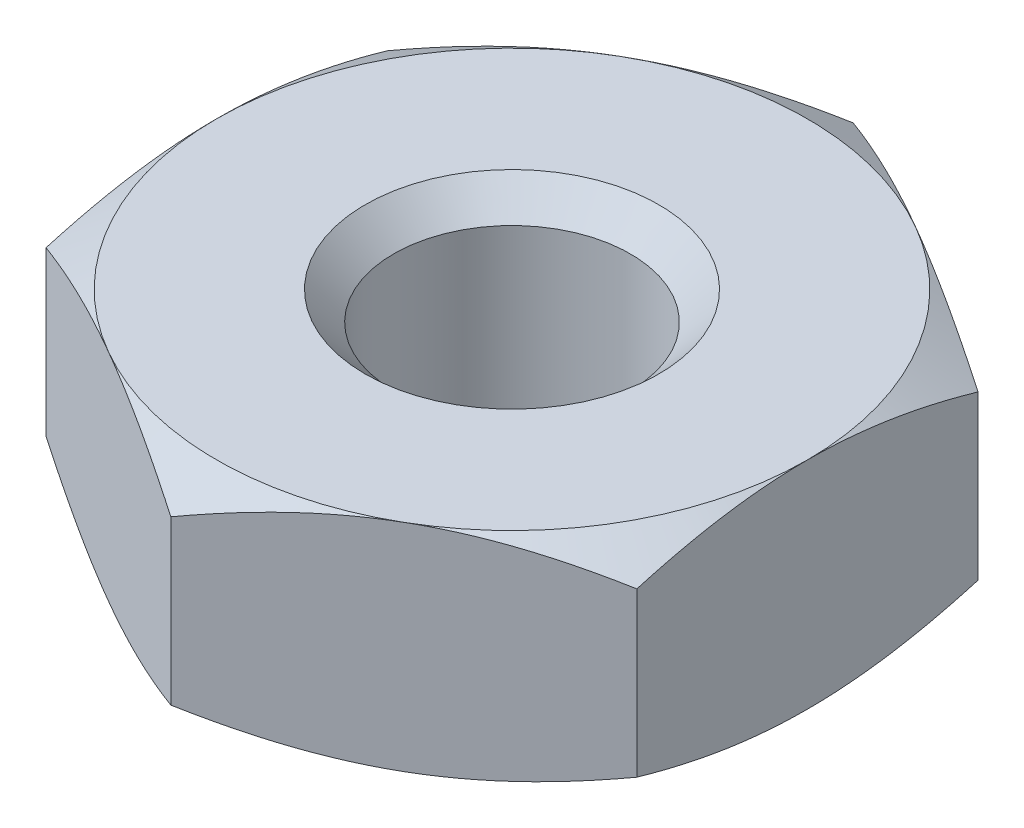
SolidWorks part; units mm, degrees
material "AISI 1020"
ref_plane "Front Plane" through (0, 0, 0) normal (0, 0, 1) x (1, 0, 0)
ref_plane "Top Plane" through (0, 0, 0) normal (0, 1, 0) x (1, 0, 0)
ref_plane "Right Plane" through (0, 0, 0) normal (1, 0, 0) x (0, 0, -1)
sketch "Sketch1" plane through (0, 0, 0) normal (0, 1, 0) x (1, 0, 0)
  line L1 (0, -4.5754) -> (3.9624, -2.2877)
  line L2 (3.9624, -2.2877) -> (3.9624, 2.2877)
  line L3 (3.9624, 2.2877) -> (0, 4.5754)
  line L4 (0, 4.5754) -> (-3.9624, 2.2877)
  line L5 (-3.9624, 2.2877) -> (-3.9624, -2.2877)
  line L6 (-3.9624, -2.2877) -> (0, -4.5754)
  circle A0 centre (0, 0) radius 3.9624 construction
  dimension "D1" = 7.9248
extrude "Boss-Extrude1" add sketch "Sketch1" along normal mid plane 2.8956 contours L4 L5 L6 L1 L2 L3
sketch "Sketch2" plane through (0, 1.4478, 0) normal (0, 1, 0) x (1, 0, 0)
  circle A0 centre (0, 0) radius 1.5875
  dimension "D1" = 3.175
extrude "Cut-Extrude1" cut sketch "Sketch2" against normal through all contours A0
sketch "Sketch3" plane through (0, 0, 0) normal (1, 0, 0) x (0, 0, -1)
  line L0 (0, 0) -> (0, -1.4478) construction
  line L1 (-2.2877, -1.4478) -> (2.2877, -1.4478) construction
  line L3 (-4.5754, 1.4478) -> (-4.5754, -1.4478) construction
  line L6 (-4.5754, -1.4478) -> (-4.5754, -1.0939)
  line L7 (-4.5754, -1.4478) -> (-3.9624, -1.4478)
  line L8 (-4.5754, -1.4478) -> (-2.2877, -1.4478) construction
  line L9 (-3.9624, -1.4478) -> (-4.5754, -1.0939)
  dimension "D1" = 30
  dimension "D2" = 7.9248
revolve "Cut-Revolve2" cut sketch "Sketch3" angle 360 about L0
mirror "Mirror2" about plane through (0, 0, 0) normal (0, 1, 0) of "Cut-Revolve2"
chamfer "Chamfer2" distance 0.381 angle 45 2 edges at (0, 1.4478, 1.5875) (0, -1.4478, 1.5875)
